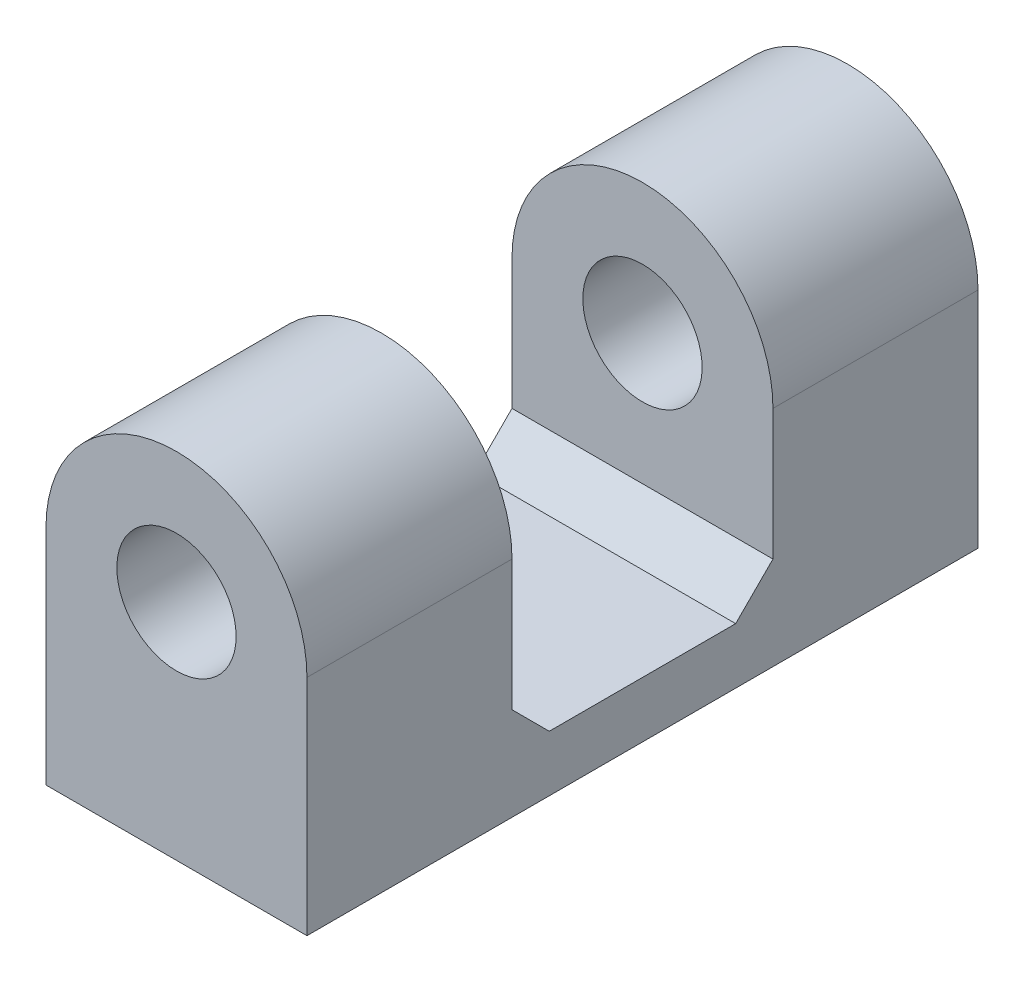
SolidWorks part; units mm, degrees
material "延性铁"
ref_plane "前视基准面" through (0, 0, 0) normal (0, 0, 1) x (1, 0, 0)
ref_plane "上视基准面" through (0, 0, 0) normal (0, 1, 0) x (1, 0, 0)
ref_plane "右视基准面" through (0, 0, 0) normal (1, 0, 0) x (0, 0, -1)
sketch "草图1" plane through (0, 0, 0) normal (0, 0, 1) x (1, 0, 0)
  line L0 (-3.5, -6) -> (-3.5, 0)
  line L3 (-3.5, -6) -> (3.5, -6)
  line L7 (3.5, -6) -> (3.5, 0)
  arc A0 (3.5, 0) -> (-3.5, 0) centre (0, 0) ccw
  circle A1 centre (0, 0) radius 1.6
  dimension "D2" = 7
  dimension "D1" = 6
  dimension "D3" = 3.5
  dimension "D4" = 3.5
extrude "凸台-拉伸1" add sketch "草图1" along normal blind 18
sketch "草图3" plane through (-3.5, 0, 0) normal (-1, 0, 0) x (0, 0, 1)
  line L0 (0, 0) -> (0, -6) construction
  line L1 (5.5, 6.8993) -> (12.5, 6.8993)
  line L2 (5.5, 6.8993) -> (5.5, -4.5)
  line L3 (5.5, -4.5) -> (12.5, -4.5)
  line L4 (12.5, 6.8993) -> (12.5, -4.5)
  line L5 (18, 0) -> (18, -6) construction
  line L6 (18, -6) -> (0, -6) construction
  dimension "D1" = 5.5
  dimension "D2" = 5.5
  dimension "D3" = 1.5
extrude "切除-拉伸2" cut sketch "草图3" against normal through all
hole_wizard "M3 螺纹孔1" positions "草图5" profile "草图4" tap size "M3" standard "GB"
sketch "草图5" plane through (0, -6, 0) normal (0, -1, 0) x (-1, 0, 0)
  line L0 (3.5, 0) -> (-3.5, 0) construction
  line L1 (3.5, -18) -> (-3.5, -18) construction
  point P0 (0, -3)
  point P2 (0, -15)
  dimension "D1" = 3
  dimension "D2" = 3
sketch "草图4" plane through (0, -6, 3) normal (1, 0, 0) x (0, 0, -1)
  line L0 (0, 0) -> (0, 4.2511)
  line L1 (0, 4.2511) -> (1.25, 3.5)
  line L2 (1.25, 3.5) -> (1.25, 0)
  line L5 (1.25, 0) -> (0, 0)
  line L10 (0, 4.2511) -> (-1.25, 3.5) construction
  line L11 (0, -6.35) -> (0, 107.95) construction
  dimension "螺纹孔钻头直径" = 2.5
  dimension "螺纹孔钻头深度" = 3.5
  dimension "导头角度" = 118
cosmetic thread "孔螺蚊线1" parameters "D1"=3.5, "D2"=3
cosmetic thread "孔螺蚊线2" parameters "D1"=3.5, "D2"=3
chamfer "倒角1" distance 1 angle 45 2 edges at (0, -4.5, 12.5) (0, -4.5, 5.5)
